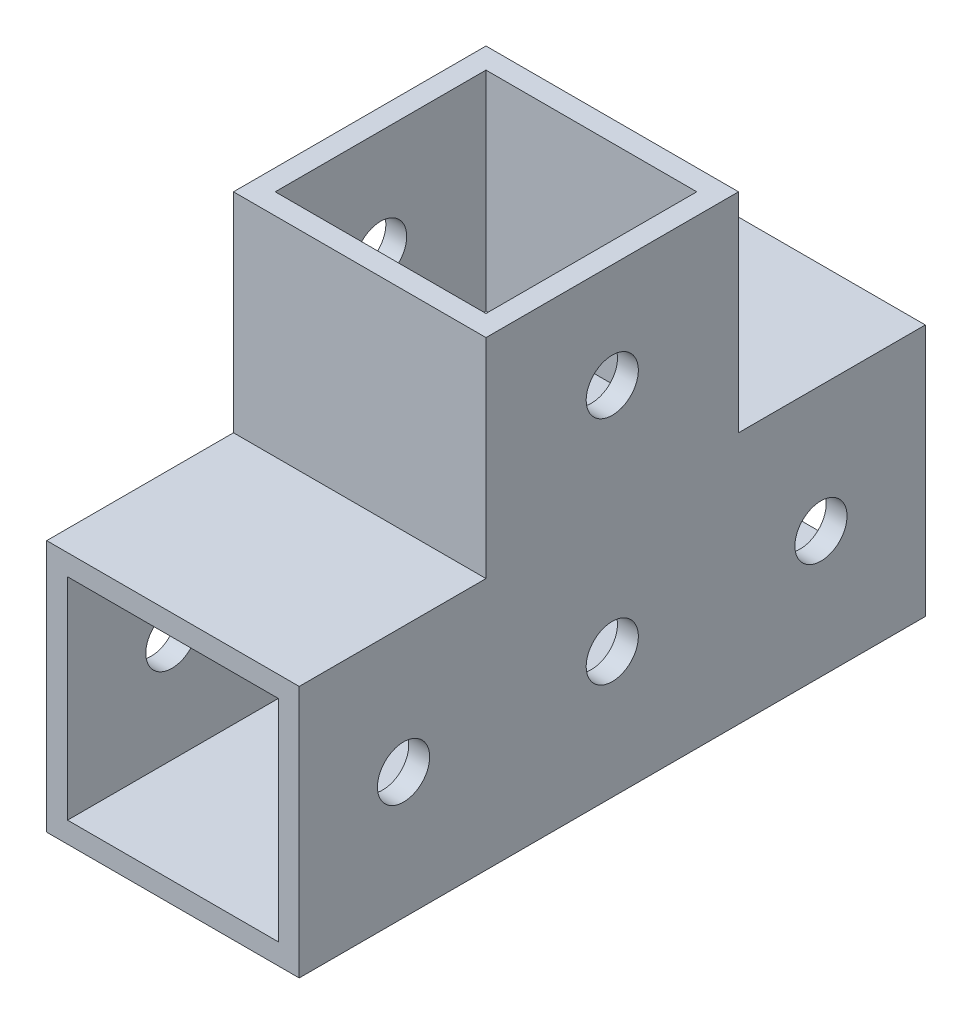
SolidWorks part; units mm, degrees
ref_plane "前视基准面" through (0, 0, 0) normal (0, 0, 1) x (1, 0, 0)
ref_plane "上视基准面" through (0, 0, 0) normal (0, 1, 0) x (1, 0, 0)
ref_plane "右视基准面" through (0, 0, 0) normal (1, 0, 0) x (0, 0, -1)
other "Configuration Table"
sketch "草图2" plane through (0, 0, 0) normal (0, 0, 1) x (1, 0, 0)
  line L0 (-12.1, 12.1) -> (12.1, 12.1)
  line L1 (-10.1, -10.1) -> (10.1, -10.1)
  line L2 (-10.1, -10.1) -> (-10.1, 10.1)
  line L3 (-10.1, 10.1) -> (10.1, 10.1)
  line L4 (10.1, -10.1) -> (10.1, 10.1)
  line L5 (-10.1, -10.1) -> (10.1, 10.1) construction
  line L6 (-10.1, 10.1) -> (10.1, -10.1) construction
  line L7 (12.1, -12.1) -> (12.1, 12.1)
  line L8 (-12.1, -12.1) -> (12.1, -12.1)
  line L9 (-12.1, -12.1) -> (-12.1, 12.1)
  point P0 (0, 0)
  dimension "D1" = 20.2
  dimension "D2" = 20.2
  dimension "D3" = 2
extrude "凸台-拉伸4" add sketch "草图2" along normal blind 100
sketch "草图6" plane through (0, 12.1, 0) normal (0, 1, 0) x (1, 0, 0)
  line L0 (-1012.1, -50) -> (48987.9, -50) construction
  line L1 (-12.1, -100) -> (-12.1, 0) construction
  line L2 (0, -1000) -> (0, 49000) construction
  line L3 (-12.1, -37.9) -> (12.1, -37.9)
  line L4 (-10.1, -60.1) -> (10.1, -60.1)
  line L5 (-10.1, -60.1) -> (-10.1, -39.9)
  line L6 (-10.1, -39.9) -> (10.1, -39.9)
  line L7 (10.1, -60.1) -> (10.1, -39.9)
  line L8 (-10.1, -60.1) -> (10.1, -39.9) construction
  line L9 (-10.1, -39.9) -> (10.1, -60.1) construction
  line L10 (12.1, -62.1) -> (12.1, -37.9)
  line L11 (-12.1, -62.1) -> (12.1, -62.1)
  line L12 (-12.1, -62.1) -> (-12.1, -37.9)
  point P5 (-12.1, -50)
  point P6 (0, -50)
  dimension "D1" = 20.2
  dimension "D2" = 20.2
  dimension "D3" = 2
extrude "凸台-拉伸5" add sketch "草图6" along normal blind 40
sketch "草图7" plane through (-12.1, 0, 0) normal (-1, 0, 0) x (0, 0, 1)
  line L0 (-1000, 0) -> (49000, 0) construction
  line L1 (50, -947.9) -> (50, 49052.1) construction
  line L2 (37.9, 52.1) -> (62.1, 52.1) construction
  circle A0 centre (10, 0) radius 2.5
  circle A1 centre (30, 0) radius 2.5
  circle A2 centre (90, 0) radius 2.5
  circle A3 centre (70, 0) radius 2.5
  circle A4 centre (50, 42.1) radius 2.5
  circle A5 centre (50, 22.1) radius 2.5
  point P8 (50, 52.1)
  point P22 (52.3637, 55.9283)
  dimension "D1" = 5
  dimension "D2" = 5
  dimension "D5" = 5
  dimension "D6" = 5
  dimension "D3" = 10
  dimension "D4" = 20
  dimension "D7" = 10
  dimension "D8" = 20
extrude "切除-拉伸1" cut sketch "草图7" against normal blind 40
sketch "草图8" plane through (12.1, 0, 0) normal (1, 0, 0) x (0, 0, -1)
  line L0 (-1100, 0) -> (48900, 0) construction
  line L1 (-100, -12.1) -> (-100, 12.1) construction
  line L2 (-50, -947.9) -> (-50, 49052.1) construction
  line L3 (-62.1, 52.1) -> (-37.9, 52.1) construction
  circle A0 centre (-50, 0) radius 2.5
  point P5 (-100, 0)
  point P10 (-50, 52.1)
  dimension "D1" = 5
extrude "切除-拉伸2" cut sketch "草图8" against normal blind 40
sketch "草图9" plane through (12.1, 0, 0) normal (1, 0, 0) x (0, 0, -1)
  line L0 (-100, 12.1) -> (-80, 12.1)
  line L1 (-100, 12.1) -> (-62.1, 12.1) construction
  line L2 (-100, -12.1) -> (0, -12.1) construction
  line L3 (-80, 12.1) -> (-100, 12.1)
  line L4 (-80, 12.1) -> (-80, -12.1)
  line L5 (-80, -12.1) -> (-100, -12.1)
  line L6 (-100, 12.1) -> (-100, -12.1)
  line L7 (-50, -947.9) -> (-50, 49052.1) construction
  line L8 (-62.1, 52.1) -> (-37.9, 52.1) construction
  line L9 (0, 12.1) -> (0, -12.1)
  line L10 (-20, -12.1) -> (0, -12.1)
  line L11 (0, 12.1) -> (-20, 12.1)
  line L12 (-20, 12.1) -> (-20, -12.1)
  point P14 (-50, 52.1)
  circle M6 centre (-10, 0) radius 2.5
  circle M9 centre (-90, 0) radius 2.5
  line M12 (0, -12.1) -> (0, 12.1)
  line M13 (0, 12.1) -> (-37.9, 12.1)
  line M17 (-62.1, 12.1) -> (-100, 12.1)
  line M18 (-100, 12.1) -> (-100, -12.1)
  line M19 (-100, -12.1) -> (0, -12.1)
  dimension "D1" = 20
extrude "切除-拉伸3" cut sketch "草图9" against normal blind 40 contours L12 M13 M19 M12 M6 | L4 M17 M18 M19 M9
sketch "草图10" plane through (12.1, 0, 0) normal (1, 0, 0) x (0, 0, -1)
  line L0 (-62.1, 52.1) -> (-62.1, 32.1)
  line L1 (-62.1, 52.1) -> (-62.1, 12.1) construction
  line L3 (-62.1, 32.1) -> (-37.9, 32.1)
  line L4 (-62.1, 32.1) -> (-62.1, 52.1)
  line L5 (-62.1, 52.1) -> (-37.9, 52.1)
  line L6 (-37.9, 32.1) -> (-37.9, 52.1)
  circle M2 centre (-50, 42.1) radius 2.5
  line M10 (-37.9, 12.1) -> (-37.9, 52.1)
  line M11 (-37.9, 52.1) -> (-62.1, 52.1)
  line M12 (-62.1, 52.1) -> (-62.1, 12.1)
  dimension "D1" = 20
extrude "切除-拉伸4" cut sketch "草图10" against normal blind 40 contours L3 M12 M10 M11 M2
